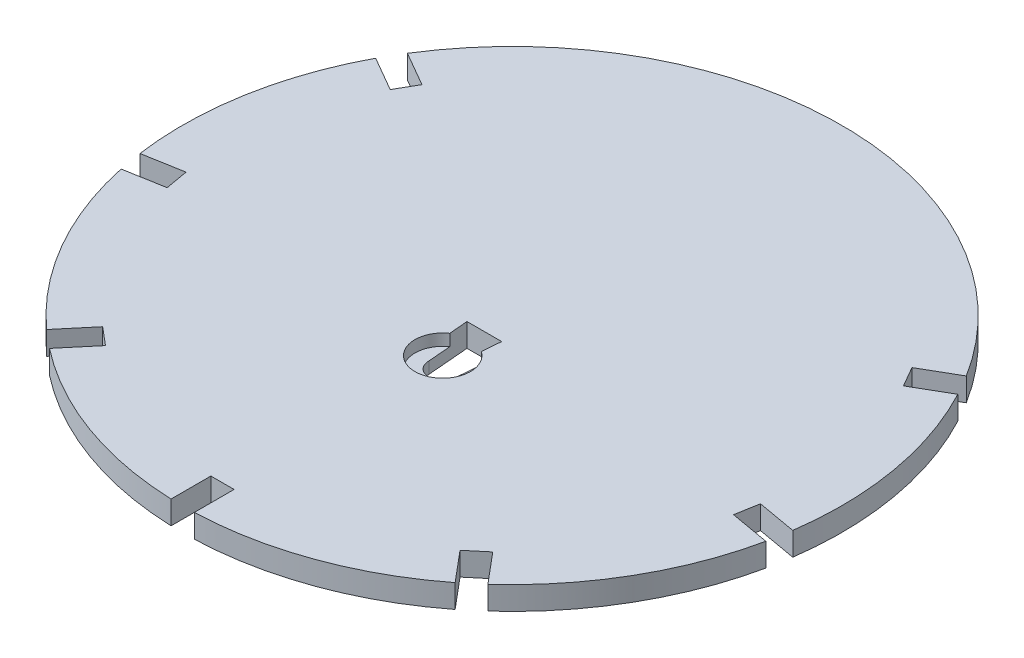
SolidWorks part; units mm, degrees
material "Balsa"
ref_plane "Front Plane" through (0, 0, 0) normal (0, 0, 1) x (1, 0, 0)
ref_plane "Top Plane" through (0, 0, 0) normal (0, 1, 0) x (1, 0, 0)
ref_plane "Right Plane" through (0, 0, 0) normal (1, 0, 0) x (0, 0, -1)
sketch "Sketch1" plane through (0, 0, 0) normal (0, 1, 0) x (1, 0, 0)
  circle A0 centre (0, 0) radius 95
  dimension "D1" = 95
extrude "Boss-Extrude1" add sketch "Sketch1" along normal blind 6.7 contours A0
sketch "Sketch2" plane through (0, 6.7, 0) normal (0, 1, 0) x (1, 0, 0)
  line L0 (0, 0) -> (82.2724, 47.5) construction
  line L1 (-5, -8) -> (5, -8)
  line L2 (70.6165, 44.6387) -> (87.937, 54.6387)
  line L3 (70.6165, 44.6387) -> (73.9665, 38.8363)
  line L4 (73.9665, 38.8363) -> (91.287, 48.8363)
  line L5 (87.937, 54.6387) -> (91.287, 48.8363)
  line L6 (-4, -20) -> (-5, -8)
  line L7 (4, -20) -> (5, -8)
  line L9 (56.2229, -61.7922) -> (69.0787, -77.1131)
  line L10 (56.2229, -61.7922) -> (51.0904, -66.0989)
  line L11 (51.0904, -66.0989) -> (63.9462, -81.4198)
  line L12 (69.0787, -77.1131) -> (63.9462, -81.4198)
  line L16 (82.7885, -11.1962) -> (102.4847, -14.6691)
  line L17 (82.7885, -11.1962) -> (81.6251, -17.7944)
  line L18 (81.6251, -17.7944) -> (101.3213, -21.2674)
  line L19 (102.4847, -14.6691) -> (101.3213, -21.2674)
  line L23 (0, 0) -> (61.0648, -72.7742) construction
  line L25 (3.35, -83.475) -> (3.35, -103.475)
  line L26 (3.35, -83.475) -> (-3.35, -83.475)
  line L29 (0, 0) -> (93.5567, -16.4966) construction
  line L30 (-3.35, -83.475) -> (-3.35, -103.475)
  line L31 (3.35, -103.475) -> (-3.35, -103.475)
  line L34 (0, 0) -> (0, -95) construction
  line L36 (-51.0904, -66.0989) -> (-63.9462, -81.4198)
  line L37 (-51.0904, -66.0989) -> (-56.2229, -61.7922)
  line L38 (-56.2229, -61.7922) -> (-69.0787, -77.1131)
  line L39 (-63.9462, -81.4198) -> (-69.0787, -77.1131)
  line L42 (0, 0) -> (-61.0648, -72.7742) construction
  line L44 (-81.6251, -17.7944) -> (-101.3213, -21.2674)
  line L45 (-81.6251, -17.7944) -> (-82.7885, -11.1962)
  line L46 (-82.7885, -11.1962) -> (-102.4847, -14.6691)
  line L47 (-101.3213, -21.2674) -> (-102.4847, -14.6691)
  line L50 (0, 0) -> (-93.5567, -16.4966) construction
  line L55 (-73.9665, 38.8363) -> (-91.287, 48.8363)
  line L56 (-73.9665, 38.8363) -> (-70.6165, 44.6387)
  line L57 (-70.6165, 44.6387) -> (-87.937, 54.6387)
  line L58 (-91.287, 48.8363) -> (-87.937, 54.6387)
  line L61 (0, 0) -> (-82.2724, 47.5) construction
  line L63 (0, 0) -> (0, 102.8222) construction
  circle A0 centre (0, 0) radius 95 construction
  arc A1 (-4, -20) -> (4, -20) centre (0, -20) ccw
  point P11 (0, -8)
  point P13 (-12.0777, 27.2748)
  point P75 (72.2915, 41.7375)
  dimension "D9" = 8
  dimension "D1" = 20
  dimension "D2" = 6.7
  dimension "D3" = 3.35
  dimension "D6" = 40
  dimension "D10" = 20
  dimension "D4" = 83.475
  dimension "D8" = 10
  dimension "D5" = 12
  dimension "D7" = 7
extrude "Cut-Extrude3" cut sketch "Sketch2" against normal blind 6.7
sketch "Sketch3" plane through (0, 6.7, 0) normal (0, 1, 0) x (1, 0, 0)
  circle A0 centre (0, -20) radius 8
  dimension "D1" = 16
extrude "Cut-Extrude4" cut sketch "Sketch3" against normal blind 3.35
equation "\"Ring inner radius\"= 80mm"
equation "\"D1@Sketch1\" = \"Bottom ring outer radius\""
equation "\"Heart cable hole radius\"= 4mm"
equation "\"Dogbone radius\"= 3.05mm"
equation "\"Tree side stock thickness\"= 6.7mm"
equation "\"D2@Sketch2\"= \"Tree side stock thickness\""
equation "\"D3@Sketch2\"= \"Tree side stock thickness\" / 2"
equation "\"Ring stock thickness\"= 6.7mm"
equation "\"D1@Boss-Extrude1\"= \"Ring stock thickness\""
equation "\"D1@Cut-Extrude3\"= \"Ring stock thickness\""
equation "\"Tree teeth\"= 15mm"
equation "\"Tree slot\"= 15mm"
equation "\"D1@Sketch2\" = \"Tree slot\" + \"Cut-Extrude Tolerance\""
equation "\"Bottom ring outer radius\"= \"Ring inner radius\" + \"Tree teeth\""
equation "\"D4@Sketch2\"=\"Ring inner radius\" + \"Base slot\" - \"Dogbone radius\"/2"
equation "\"D9@Sketch2\" = \"Heart cable hole radius\" * 2"
equation "\"Cut-Extrude Tolerance\"= 5mm"
equation "\"Base slot\"= 5mm"
equation "\"D1@Cut-Extrude4\"= \"Ring stock thickness\" / 2"
